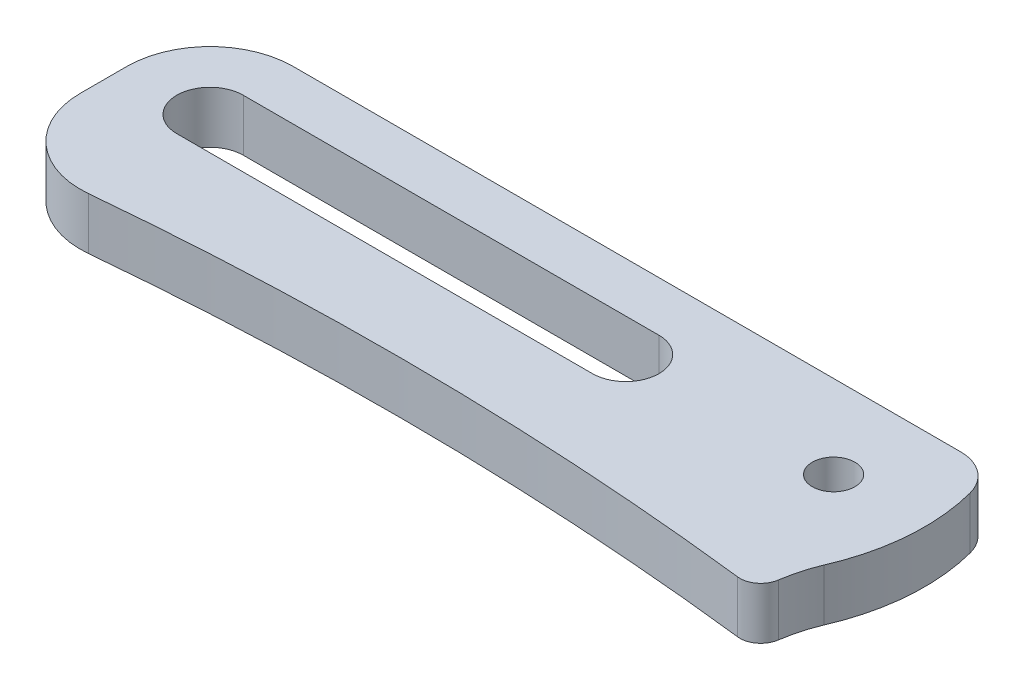
SolidWorks part; units mm, degrees
material "Thornel Mat VMA"
ref_plane "前视基准面" through (0, 0, 0) normal (0, 0, 1) x (1, 0, 0)
ref_plane "上视基准面" through (0, 0, 0) normal (0, 1, 0) x (1, 0, 0)
ref_plane "右视基准面" through (0, 0, 0) normal (1, 0, 0) x (0, 0, -1)
other "Configuration Table"
sketch "草图1" plane through (0, 0, 0) normal (0, 1, 0) x (1, 0, 0)
  line L0 (0, 0) -> (20, 0) construction
  line L1 (0, 1.6) -> (20, 1.6)
  line L2 (0, -1.6) -> (20, -1.6)
  line L3 (0, 0) -> (30, 0) construction
  line L4 (0, 4) -> (30, 4)
  line L5 (0, -4) -> (30, -4)
  arc A0 (0, 1.6) -> (0, -1.6) centre (0, 0) ccw
  arc A1 (20, -1.6) -> (20, 1.6) centre (20, 0) ccw
  circle A2 centre (30, 0) radius 1.025
  arc A3 (0, 4) -> (0, -4) centre (0, 0) ccw
  arc A4 (30, -4) -> (30, 4) centre (30, 0) ccw
  point P3 (10, 0)
  point P10 (15, 0)
  dimension "D2" = 1.6
  dimension "D3" = 2.05
  dimension "D5" = 4
  dimension "D1" = 20
  dimension "D4" = 30
extrude "凸台-拉伸1" add sketch "草图1" along normal blind 2.5
sketch "草图4" plane through (0, 0, 0) normal (0, 1, 0) x (1, 0, 0)
  line L6 (30, 4) -> (35, 4)
  line L7 (30, 4) -> (30, -4)
  line L8 (30, -4) -> (35, -4)
  line L9 (35, 4) -> (35, -4)
  circle A0 centre (30, 0) radius 1.025 construction
  circle A1 centre (30, 0) radius 1.025
  point P14 (35, -4)
  dimension "D2" = 8
  dimension "D1" = 5
extrude "凸台-拉伸3" add sketch "草图4" along normal blind 2.5
sketch "草图2" plane through (0, 0, 0) normal (0, -1, 0) x (1, 0, 0)
  line L0 (-4, 0) -> (-4, 6.7)
  line L1 (-4, 6.7) -> (33, 6.7)
  line L2 (0, 1.6) -> (20, 1.6) construction
  line L3 (0, 4) -> (35, 4) construction
  line L4 (14.5, 155.5548) -> (11.8915, 29.6625) construction
  line L5 (11.8915, 25.5318) -> (11.8915, 5.5775) construction
  arc A0 (0, 4) -> (0, -4) centre (0, 0) ccw construction
  arc A1 (33, 6.7) -> (33.5417, 4) centre (40, 6.7) ccw
  circle A2 centre (14.5, 155.5548) radius 150
  arc A5 (2.9376, 26.3385) -> (15.1657, 26.2669) centre (9.1632, 45.3448) ccw construction
  arc M4 (0, 4) -> (0, -4) centre (0, 0) ccw
  line M7 (35, 4) -> (0, 4)
  dimension "D3" = 300
  dimension "D4" = 7
  dimension "D1" = 6.7
  dimension "D2" = 37
extrude "凸台-拉伸2" add sketch "草图2" against normal blind 2.5 contours A2 L0 A1 M4 M7
fillet "圆角1" radius 4 1 edges at (-4, 1.25, 6.7)
sketch "草图5" plane through (0, 2.5, 0) normal (0, 1, 0) x (1, 0, 0)
  line L0 (33.5417, -4) -> (35, -4) construction
  line L1 (35, 4) -> (35, -4) construction
  line L2 (35, 4) -> (0, 4) construction
  line L3 (33.5417, -4) -> (35, -4)
  line L4 (35, 4) -> (35, -4)
  line L5 (35, 4) -> (0, 4)
  circle A0 centre (24.3765, 0) radius 10
  line M6 (33.5417, -4) -> (35, -4)
  line M7 (35, -4) -> (35, 4)
  line M8 (35, 4) -> (0, 4)
  dimension "D1" = 20
extrude "切除-拉伸1" cut sketch "草图5" against normal blind 2.5 contours A0 M6 M7 M8
fillet "圆角3" radius 1 1 edges at (33, 1.25, 6.7)
fillet "圆角4" radius 2 1 edges at (33.5417, 1.25, -4)
